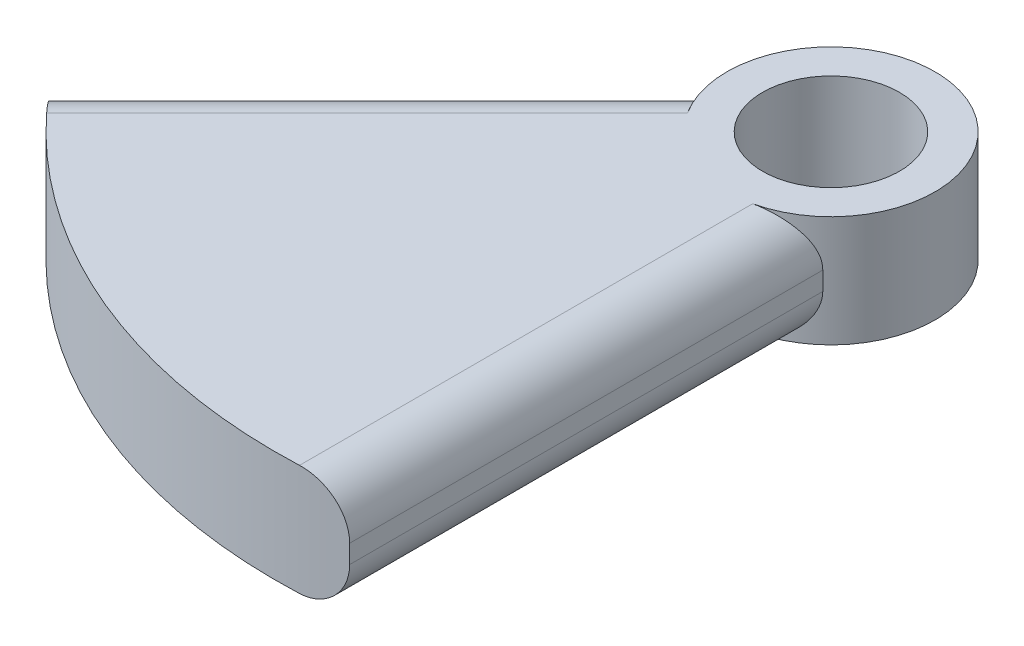
SolidWorks part; units mm, degrees
ref_plane "Front Plane" through (0, 0, 0) normal (0, 0, 1) x (1, 0, 0)
ref_plane "Top Plane" through (0, 0, 0) normal (0, 1, 0) x (1, 0, 0)
ref_plane "Right Plane" through (0, 0, 0) normal (1, 0, 0) x (0, 0, -1)
sketch "Sketch1" plane through (0, 0, 0) normal (0, 1, 0) x (1, 0, 0)
  line L0 (0, 0) -> (-53.8815, -53.8815) construction
  line L1 (0, 0) -> (0, -76.2) construction
  line L2 (-14.2654, -0.795) -> (-60.1941, -46.7237)
  line L3 (9.525, -10.6493) -> (9.525, -75.6023)
  circle A0 centre (0, 0) radius 9.398
  circle A1 centre (0, 0) radius 14.2875
  circle A2 centre (0, 0) radius 76.2 construction
  arc A3 (-60.1941, -46.7237) -> (9.525, -75.6023) centre (0, 0) ccw
  dimension "D1" = 18.796
  dimension "D2" = 28.575
  dimension "D3" = 45
  dimension "D4" = 76.2
  dimension "D5" = 9.525
  dimension "D6" = 9.525
extrude "Boss-Extrude2" add sketch "Sketch1" along normal blind 15.24 contours L2 A3 L3 A1 | A1 A0
fillet "Fillet1" radius 6.35 4 edges at (-37.2297, 15.24, 23.7594) (-37.2297, 0, 23.7594) (9.525, 0, 43.1258) (9.525, 15.24, 43.1258)
